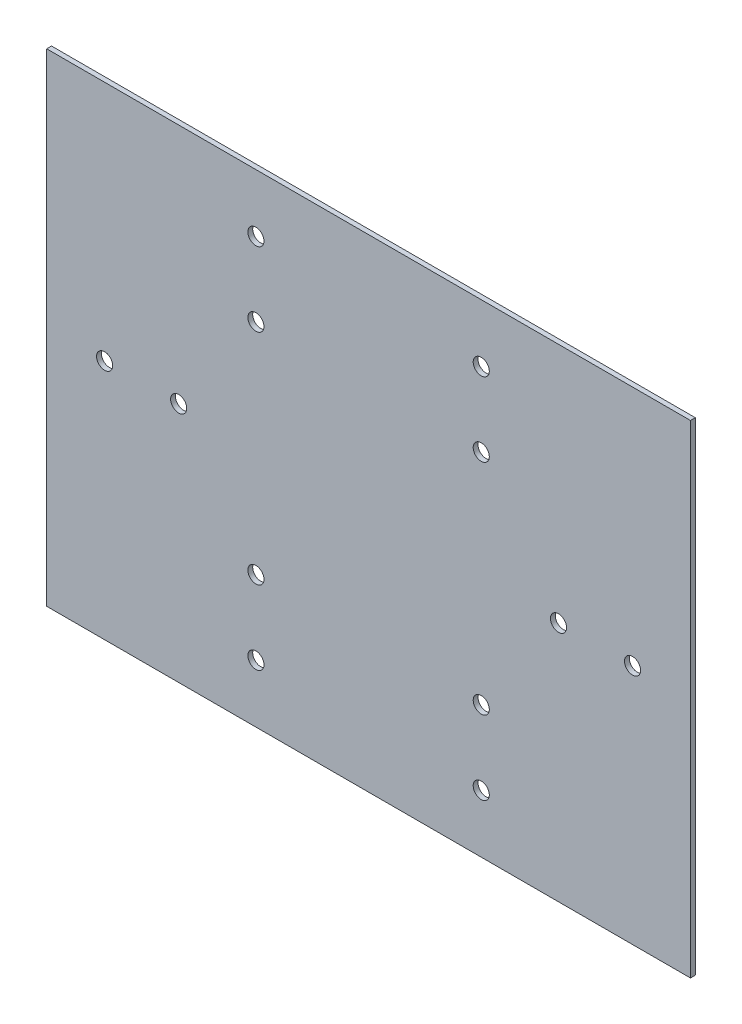
SolidWorks part; units mm, degrees
ref_plane "前视基准面" through (0, 0, 0) normal (0, 0, 1) x (1, 0, 0)
ref_plane "上视基准面" through (0, 0, 0) normal (0, 1, 0) x (1, 0, 0)
ref_plane "右视基准面" through (0, 0, 0) normal (1, 0, 0) x (0, 0, -1)
sketch "草图1" plane through (0, 0, 0) normal (0, 0, 1) x (1, 0, 0)
  line L0 (-100, 0) -> (-82, 0) construction
  line L1 (-100, -75) -> (100, -75)
  line L2 (-100, -75) -> (-100, 75)
  line L3 (-100, 75) -> (100, 75)
  line L4 (100, -75) -> (100, 75)
  line L5 (-100, -75) -> (100, 75) construction
  line L6 (-100, 75) -> (100, -75) construction
  line L7 (-82, 0) -> (-59, 0) construction
  line L8 (0, 0) -> (0, 20) construction
  line L9 (-100, -75) -> (-35, -75) construction
  line L10 (-35, -75) -> (-35, -57) construction
  line L11 (-35, -57) -> (-35, -34) construction
  circle A0 centre (-82, 0) radius 2.5
  circle A1 centre (-59, 0) radius 2.5
  circle A2 centre (59, 0) radius 2.5
  circle A3 centre (82, 0) radius 2.5
  circle A4 centre (-35, -34) radius 2.5
  circle A5 centre (-35, -57) radius 2.5
  circle A6 centre (35, -57) radius 2.5
  circle A7 centre (35, -34) radius 2.5
  circle A8 centre (35, 57) radius 2.5
  circle A9 centre (35, 34) radius 2.5
  circle A10 centre (-35, 57) radius 2.5
  circle A11 centre (-35, 34) radius 2.5
  point P0 (0, 0)
extrude "凸台-拉伸1" add sketch "草图1" along normal blind 1.5
